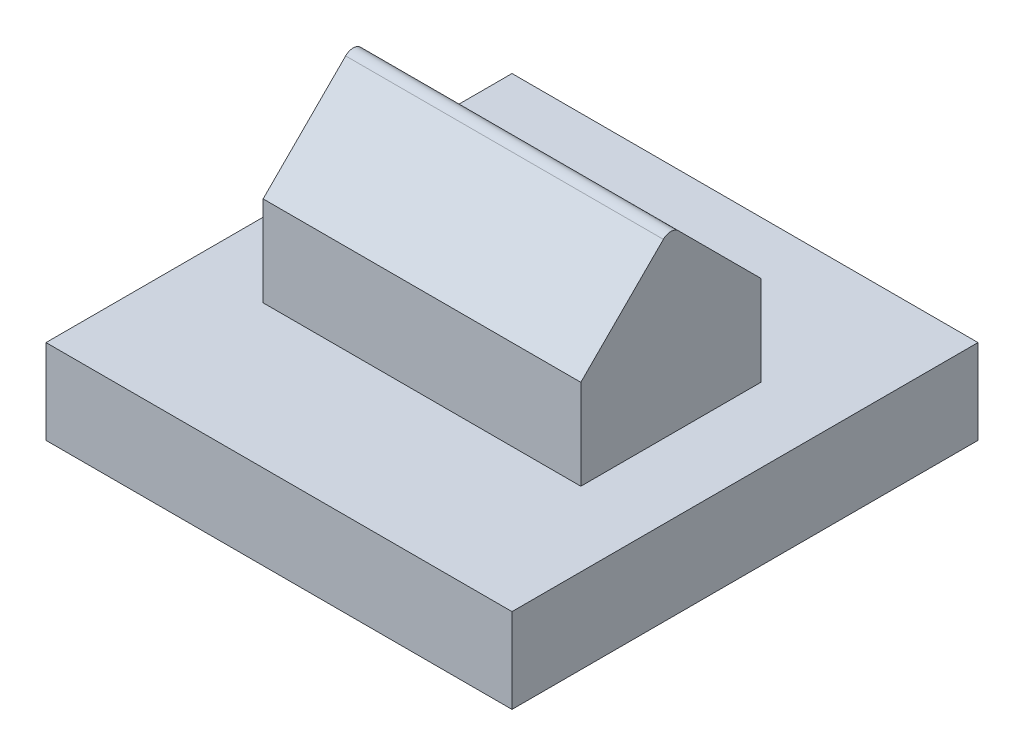
SolidWorks part; units mm, degrees
ref_plane "Plano frontal" through (0, 0, 0) normal (0, 0, 1) x (1, 0, 0)
ref_plane "Plano superior" through (0, 0, 0) normal (0, 1, 0) x (1, 0, 0)
ref_plane "Plano direito" through (0, 0, 0) normal (1, 0, 0) x (0, 0, -1)
sketch "Esboço2" plane through (0, 0, 0) normal (0, 0, 1) x (1, 0, 0)
  line L1 (0, 379.3949) -> (0, 0) construction
  line L2 (0, -8) -> (0, -18803.5335) construction
  line L3 (0, 0) -> (22, 0)
  line L5 (0, -8) -> (22, -8)
  line L6 (22, 0) -> (22, -8)
  line L7 (0, 0) -> (-22, 0)
  line L9 (0, -8) -> (-22, -8)
  line L10 (-22, 0) -> (-22, -8)
  dimension "D1" = 44
  dimension "D2" = 8
extrude "Ressalto-extrusão1" add sketch "Esboço2" along normal blind 22 and the other way blind 22
sketch "Esboço4" plane through (0, 0, 0) normal (1, 0, 0) x (0, 0, -1)
  line L1 (-8.5, 8.5) -> (-0.7071, 16.2929)
  line L3 (-8.5, 8.5) -> (-8.5, 0)
  line L7 (8.5, 8.5) -> (8.5, 0)
  line L8 (8.5, 0) -> (0, 0)
  line L9 (-8.5, 0) -> (0, 0)
  line L10 (-8.3888, 18.139) -> (-565.9228, -49978.7525) construction
  line L11 (8.5, 8.5) -> (0.7071, 16.2929)
  line L12 (0.0451, 13.5838) -> (0.0451, 50013.5838) construction
  line L13 (8.4791, 18.2292) -> (8.4791, -49981.7708) construction
  arc A2 (0.7071, 16.2929) -> (-0.7071, 16.2929) centre (0, 15.5858) ccw
  dimension "D1" = 1
  dimension "D2" = 17
  dimension "D3" = 45
  dimension "D4" = 45
extrude "Ressalto-extrusão2" add sketch "Esboço4" against normal blind 15 and the other way blind 15
